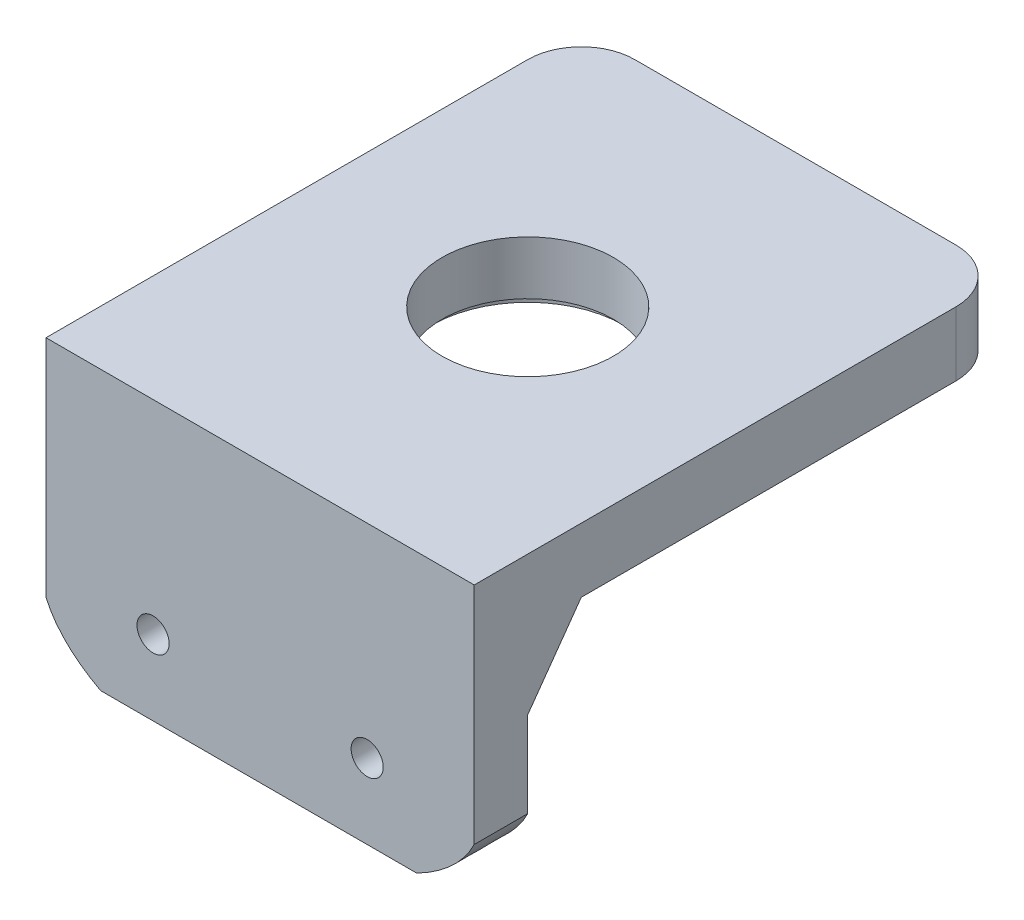
SolidWorks part; units mm, degrees
ref_plane "Front Plane" through (0, 0, 0) normal (0, 0, 1) x (1, 0, 0)
ref_plane "Top Plane" through (0, 0, 0) normal (0, 1, 0) x (1, 0, 0)
ref_plane "Right Plane" through (0, 0, 0) normal (1, 0, 0) x (0, 0, -1)
sketch "Sketch1" plane through (0, 0, 0) normal (0, 1, 0) x (1, 0, 0)
  line L1 (-20, 25) -> (20, 25)
  line L2 (-20, 25) -> (-20, -25)
  line L3 (-20, -25) -> (20, -25)
  line L4 (20, 25) -> (20, -25)
  line L5 (-20, 25) -> (20, -25) construction
  line L6 (-20, -25) -> (20, 25) construction
  point P0 (0, 0)
  dimension "D1" = 40
  dimension "D2" = 50
extrude "Boss-Extrude1" add sketch "Sketch1" along normal blind 6
sketch "Sketch3" plane through (0, 6, 0) normal (0, 1, 0) x (1, 0, 0)
  line L0 (-20, -25) -> (20, -25) construction
  circle A0 centre (0, 0) radius 8
  point P0 (0, 0)
  dimension "D2" = 16
  dimension "D1" = 25
extrude "Cut-Extrude1" cut sketch "Sketch3" against normal blind 9
sketch "Sketch4" plane through (0, 0, 0) normal (0, -1, 0) x (1, 0, 0)
  line L0 (-20, -25) -> (-20, 25) construction
  line L1 (20, 25) -> (-20, 25)
  line L2 (20, 25) -> (20, 20)
  line L3 (20, 20) -> (-20, 20)
  line L4 (-20, 25) -> (-20, 20)
  dimension "D1" = 5
extrude "Boss-Extrude2" add sketch "Sketch4" along normal blind 20
sketch "Sketch5" plane through (20, 0, 0) normal (1, 0, 0) x (0, 0, -1)
  line L0 (-20, 0) -> (25, 0) construction
  line L1 (-20, -20) -> (-20, 0) construction
  line L2 (-15, 0) -> (-20, 0)
  line L3 (-20, 0) -> (-20, -7)
  line L4 (-20, -7) -> (-15, 0)
  point P0 (-15, 0)
  point P1 (-20, -7)
  dimension "D1" = 5
  dimension "D2" = 7
extrude "Boss-Extrude3" add sketch "Sketch5" against normal blind 40
sketch "Sketch6" plane through (0, 0, 20) normal (0, 0, -1) x (-1, 0, 0)
  line L0 (-20, -20) -> (-20, -7) construction
  line L1 (20, -20) -> (20, -7) construction
  line L2 (20, -20) -> (-20, -20) construction
  circle A0 centre (-10, -13) radius 1.5
  circle A1 centre (10, -13) radius 1.5
  point P0 (10, -13)
  point P1 (-10, -13)
  dimension "D5" = 3
  dimension "D6" = 3
  dimension "D1" = 10
  dimension "D2" = 10
  dimension "D3" = 7
  dimension "D4" = 7
extrude "Cut-Extrude2" cut sketch "Sketch6" against normal through all
sketch "Sketch7" plane through (0, 6, 0) normal (0, 1, 0) x (1, 0, 0)
  line L0 (-20, 25) -> (-20, -25) construction
  line L1 (20, 25) -> (-20, 25) construction
  line L2 (20, -25) -> (20, 25) construction
  line L3 (-20, 20) -> (-20, 25)
  line L4 (-20, 25) -> (-15, 25)
  line L5 (15, 25) -> (20, 25)
  line L6 (20, 25) -> (20, 20)
  arc A0 (-15, 25) -> (-20, 20) centre (-15, 20) ccw
  arc A1 (20, 20) -> (15, 25) centre (15, 20) ccw
  point P0 (-20, 20)
  point P1 (-15, 25)
  point P4 (15, 25)
  point P7 (20, 20)
  dimension "D1" = 5
  dimension "D2" = 5
  dimension "D3" = 5
  dimension "D4" = 5
extrude "Cut-Extrude3" cut sketch "Sketch7" against normal through all
sketch "Sketch8" plane through (0, 0, 20) normal (0, 0, -1) x (-1, 0, 0)
  line L0 (-20, -20) -> (-20, -7) construction
  line L1 (20, -20) -> (-20, -20) construction
  line L2 (20, -20) -> (20, -7) construction
  line L3 (20, -15) -> (15.2918, -25.8047) construction
  line L4 (15.2918, -25.8047) -> (-14.7082, -25.8047) construction
  line L6 (-14.7082, -25.8047) -> (-20, -15) construction
  line L7 (20, -15) -> (20, -20)
  line L8 (20, -20) -> (-20, -20)
  line L9 (-20, -20) -> (-20, -15)
  spline S0 degree 3 poles (20, -15) (15.2918, -25.8047) (-14.7082, -25.8047) (-20, -15) knots 0 0 0 0 1 1 1 1
  point P0 (-20, -15)
  point P1 (-15, -20)
  point P4 (20, -15)
  point P7 (15, -20)
  line M7 (20, -20) -> (20, -7)
  line M9 (-20, -7) -> (-20, -20)
  line M10 (-20, -20) -> (20, -20)
  dimension "D1" = 5
  dimension "D2" = 5
  dimension "D3" = 5
  dimension "D4" = 5
extrude "Cut-Extrude4" cut sketch "Sketch8" against normal through all contours S0 M7 M10 | S0 M10 M9
sketch "Sketch9" plane through (0, 0, 0) normal (0, -1, 0) x (1, 0, 0)
  circle A0 centre (0, 0) radius 9
  dimension "D1" = 18
extrude "Cut-Extrude5" cut sketch "Sketch9" against normal blind 1
